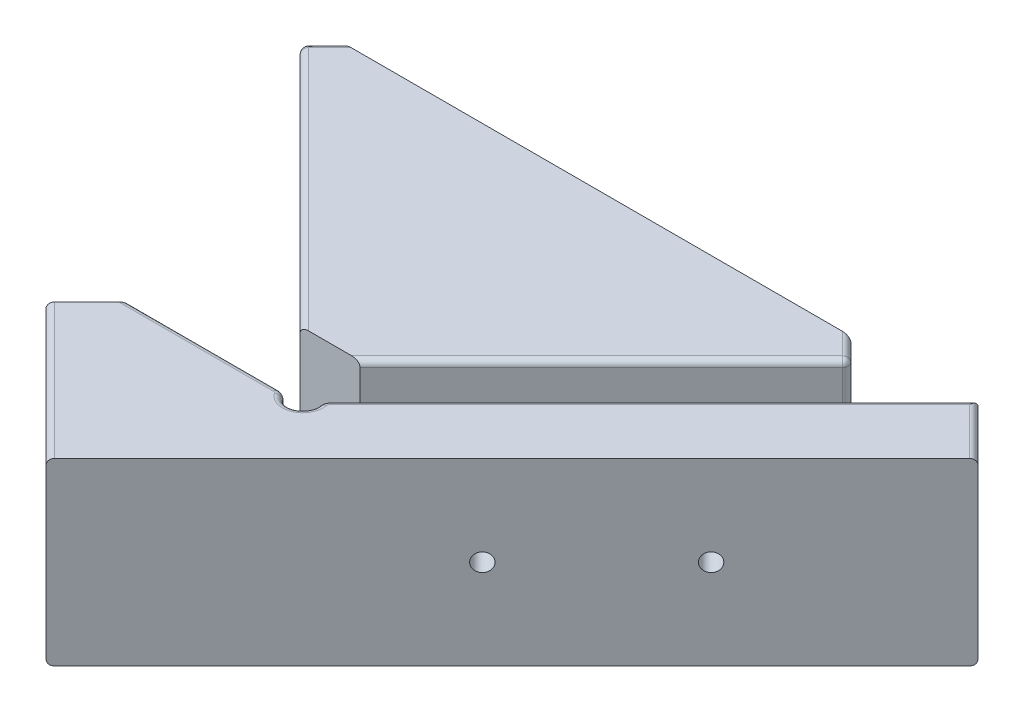
SolidWorks part; units mm, degrees
ref_plane "Front Plane" through (0, 0, 0) normal (0, 0, 1) x (1, 0, 0)
ref_plane "Top Plane" through (0, 0, 0) normal (0, 1, 0) x (1, 0, 0)
ref_plane "Right Plane" through (0, 0, 0) normal (1, 0, 0) x (0, 0, -1)
sketch "Sketch1" plane through (0, 0, 0) normal (0, 1, 0) x (1, 0, 0)
  line L0 (-24.7487, 0) -> (24.7487, 0)
  line L1 (24.7487, 0) -> (0, -24.7487)
  line L2 (0, -24.7487) -> (-24.7487, 0)
  point P7 (0, 0)
  dimension "D1" = 35
extrude "Boss-Extrude1" add sketch "Sketch1" along normal blind 15
sketch "Sketch3" plane through (0, 0, 0) normal (0, -1, 0) x (1, 0, 0)
  line L0 (-2.5, 22.2487) -> (0, 24.7487)
  line L1 (0, 24.7487) -> (2.5, 22.2487)
  line L2 (2.5, 22.2487) -> (-2.5, 22.2487)
  line L3 (0, 24.7487) -> (-24.7487, 0)
  line L4 (-24.7487, 0) -> (24.7487, 0)
  line L5 (24.7487, 0) -> (0, 24.7487)
  line L6 (0, 24.7487) -> (-24.7487, 0) construction
  line L7 (-24.7487, 0) -> (24.7487, 0) construction
  line L8 (24.7487, 0) -> (0, 24.7487) construction
  line L9 (-24.7487, 0) -> (0, 24.7487) construction
  line L10 (-24.7487, 0) -> (-22.981, 1.7678)
  line L11 (-22.981, 1.7678) -> (-21.2132, 0)
  line L12 (-21.2132, 0) -> (-24.7487, 0)
  line L14 (24.7487, 0) -> (21.2132, 0)
  line L15 (21.2132, 0) -> (22.981, 1.7678)
  line L16 (22.981, 1.7678) -> (24.7487, 0)
  dimension "D2" = 2.5
  dimension "D3" = 2.5
  dimension "D4" = 2.5
  dimension "D1" = 0
sketch "Sketch9" plane through (12.3744, 0, 12.3744) normal (0.7071, 0, 0.7071) x (0.7071, 0, -0.7071)
  line L0 (-17.5, 15) -> (0, 0) construction
  line L1 (0, 0) -> (17.5, 15) construction
  line L2 (-17.5, 0) -> (0, 15) construction
  line L3 (0, 15) -> (17.5, 0) construction
  line L4 (-17.5, 0) -> (17.5, 0)
  line L5 (17.5, 0) -> (17.5, 15)
  line L6 (17.5, 15) -> (-17.5, 15)
  line L7 (-17.5, 15) -> (-17.5, 0)
  line L8 (-17.5, 0) -> (17.5, 0) construction
  line L9 (17.5, 0) -> (17.5, 15) construction
  line L10 (17.5, 15) -> (-17.5, 15) construction
  line L11 (-17.5, 15) -> (-17.5, 0) construction
  circle A0 centre (-6.75, 7.5) radius 2
  circle A1 centre (6.75, 7.5) radius 2
  point P13 (-8.75, 7.5)
  point P21 (-17.5, 7.5)
  point P23 (8.75, 7.5)
  dimension "D2" = 4
  dimension "D1" = 0
sketch "Sketch10" plane through (-12.3744, 0, 12.3744) normal (-0.7071, 0, 0.7071) x (0.7071, 0, 0.7071)
  line L0 (-17.5, 15) -> (0, 0) construction
  line L1 (0, 0) -> (17.5, 15) construction
  line L2 (-17.5, 0) -> (0, 15) construction
  line L3 (0, 15) -> (17.5, 0) construction
  line L4 (-17.5, 0) -> (17.5, 0)
  line L5 (17.5, 0) -> (17.5, 15)
  line L6 (17.5, 15) -> (-17.5, 15)
  line L7 (-17.5, 15) -> (-17.5, 0)
  line L8 (-17.5, 0) -> (17.5, 0) construction
  line L9 (17.5, 0) -> (17.5, 15) construction
  line L10 (17.5, 15) -> (-17.5, 15) construction
  line L11 (-17.5, 15) -> (-17.5, 0) construction
  circle A0 centre (-6.75, 7.5) radius 2
  circle A1 centre (6.75, 7.5) radius 2
  point P14 (8.75, 7.5)
  point P15 (-8.75, 7.5)
  point P16 (17.5, 7.5)
  dimension "D2" = 4
  dimension "D1" = 0
extrude "Cut-Extrude5" cut sketch "Sketch9" against normal up to surface (22.25 mm away)
extrude "Cut-Extrude6" cut sketch "Sketch10" against normal up to surface (12.75 mm away)
extrude "Cut-Extrude7" cut sketch "Sketch3" against normal up to next
fillet "Fillet1" radius 0.5 10 edges at (-12.7405, 15, 12.0083) (-22.0971, 15, 0.8839) (-12.7405, 0, 12.0083) (12.7405, 0, 12.0083) (12.7405, 15, 12.0083) (22.0971, 15, 0.8839) (-22.0971, 0, 0.8839) (22.0971, 0, 0.8839) (22.981, 7.5, 1.7678) (-22.981, 7.5, 1.7678)
ref_plane "Plane1" through (-8.1317, 0, 8.1317) normal (-0.7071, 0, 0.7071) x (0.7071, 0, 0.7071)
sketch "Sketch11" plane through (-8.1317, 0, 8.1317) normal (-0.7071, 0, 0.7071) x (0.7071, 0, 0.7071)
  circle A0 centre (6.75, 7.5) radius 2 construction
  circle A1 centre (-6.75, 7.5) radius 2 construction
  circle A2 centre (6.75, 7.5) radius 2 construction
  circle A3 centre (-6.75, 7.5) radius 2 construction
  circle A4 centre (-6.75, 7.5) radius 3.5
  circle A5 centre (6.75, 7.5) radius 3.5
  dimension "D1" = 7
extrude "Cut-Extrude8" cut sketch "Sketch11" against normal up to surface (8.25 mm away)
ref_plane "Plane2" through (8.1317, 0, 8.1317) normal (0.7071, 0, 0.7071) x (0.7071, 0, -0.7071)
sketch "Sketch12" plane through (8.1317, 0, 8.1317) normal (0.7071, 0, 0.7071) x (0.7071, 0, -0.7071)
  circle A0 centre (-6.75, 7.5) radius 2 construction
  circle A1 centre (6.75, 7.5) radius 2 construction
  circle A2 centre (-6.75, 7.5) radius 2 construction
  circle A3 centre (6.75, 7.5) radius 2 construction
  circle A4 centre (6.75, 7.5) radius 3.5
  circle A5 centre (-6.75, 7.5) radius 3.5
  dimension "D1" = 7
extrude "Cut-Extrude9" cut sketch "Sketch12" against normal up to surface (1.25 mm away)
ref_plane "Plane3" through (19.4454, 0, 19.4454) normal (0.7071, 0, 0.7071) x (0.7071, 0, -0.7071)
sketch "Sketch14" plane through (19.4454, 0, 19.4454) normal (0.7071, 0, 0.7071) x (0.7071, 0, -0.7071)
  line L0 (14.5, 0) -> (-14.4645, 0) construction
  line L1 (15, 14.5) -> (15, 0.5) construction
  line L2 (-14.4645, 15) -> (14.5, 15) construction
  line L3 (-17.5, 14.5) -> (-17.5, 0.5) construction
  line L4 (14.5, 0) -> (-14.4645, 0) construction
  line L5 (15, 14.5) -> (15, 0.5) construction
  line L6 (-14.4645, 15) -> (14.5, 15) construction
  line L7 (-17.5, 14.5) -> (-17.5, 0.5) construction
  line L8 (-32.5, 15) -> (22.5, 15)
  line L9 (22.5, 15) -> (22.5, 0)
  line L10 (22.5, 0) -> (-32.5, 0)
  line L11 (-32.5, 0) -> (-32.5, 15)
  circle A0 centre (6.75, 7.5) radius 2 construction
  circle A1 centre (-6.75, 7.5) radius 2 construction
  circle A2 centre (6.75, 7.5) radius 2 construction
  circle A3 centre (-6.75, 7.5) radius 2 construction
  circle A4 centre (-6.75, 7.5) radius 0.75
  circle A5 centre (6.75, 7.5) radius 0.75
  dimension "D1" = 1.5
  dimension "D2" = 55
  dimension "D3" = 15
extrude "Boss-Extrude2" add sketch "Sketch14" against normal blind 6 separate body
sketch "Sketch15" plane through (0, 15, 0) normal (0, 1, 0) x (1, 0, 0)
  line L0 (-1.7929, -22.2487) -> (1.7929, -22.2487) construction
  line L1 (-1.7929, -22.2487) -> (1.7929, -22.2487) construction
  line L2 (-7.7782, -38.1838) -> (-18.3848, -27.5772) construction
  line L3 (-18.3848, -27.5772) -> (2.8284, -27.5772) construction
  line L4 (-2.5, -22.2487) -> (-1.7929, -22.2487) construction
  line L5 (-2.5, -22.2487) -> (-1.7929, -22.2487) construction
  line L6 (-2.8861, -21.8626) -> (11.9514, -36.7002) construction
  line L7 (-2.5, -22.2487) -> (-22.6274, -2.1213) construction
  line L8 (31.1127, 0.7071) -> (-7.7782, -38.1838) construction
  line L9 (31.1127, 0.7071) -> (-7.7782, -38.1838) construction
  line L10 (-7.7782, -38.1838) -> (2.8284, -27.5772)
  line L11 (2.8284, -27.5772) -> (-11.3137, -27.5772)
  line L12 (-11.3137, -27.5772) -> (-14.8492, -31.1127)
  line L13 (-14.8492, -31.1127) -> (-7.7782, -38.1838)
  dimension "D1" = 45
  dimension "D2" = 45
  dimension "D3" = 10
extrude "Boss-Extrude3" add sketch "Sketch15" against normal up to surface (15 mm away) up to face at (13.7886, 0, 20.8597)
sketch "Sketch16" plane through (0, 15, 0) normal (0, 1, 0) x (1, 0, 0)
  line L0 (2.8284, -27.5772) -> (-11.3137, -27.5772) construction
  line L1 (31.1127, 0.7071) -> (2.8284, -27.5772) construction
  line L2 (2.6754, -27.2076) -> (2.8284, -27.5772) construction
  line L3 (2.8284, -27.5772) -> (-11.3137, -27.5772) construction
  line L4 (31.1127, 0.7071) -> (2.8284, -27.5772) construction
  line L5 (1.0788, -27.5772) -> (2.8284, -27.5772)
  line L6 (2.8284, -27.5772) -> (4.0656, -26.34)
  arc A1 (1.6928, -27.8966) -> (1.0788, -27.5772) centre (1.0788, -28.3272) ccw
  arc A2 (1.6928, -27.8966) -> (3.8573, -27) centre (2.6754, -27.2076) ccw
  arc A3 (4.0656, -26.34) -> (3.8573, -27) centre (4.596, -26.8703) ccw
  dimension "D1" = 67.5
  dimension "D2" = 0.75
  dimension "D3" = 1.2
  dimension "D4" = 0.4
extrude "Cut-Extrude10" cut sketch "Sketch16" against normal up to surface (15 mm away) up to face at (6.5997, 0, 21.9203)
fillet "Fillet2" radius 0.5 14 edges at (17.5892, 0, 12.8164) (17.5892, 15, 12.8164) (3.8807, 0, 26.6445) (1.4248, 0, 27.6618) (3.1346, 0, 28.3163) (3.8807, 15, 26.6445) (1.4248, 15, 27.6618) (3.1346, 15, 28.3163) (-5.1175, 15, 27.5772) (-5.1175, 0, 27.5772) (-9.1924, 15, 36.7696) (-9.1924, 0, 36.7696) (33.234, 0, 1.4142) (33.234, 15, 1.4142)
